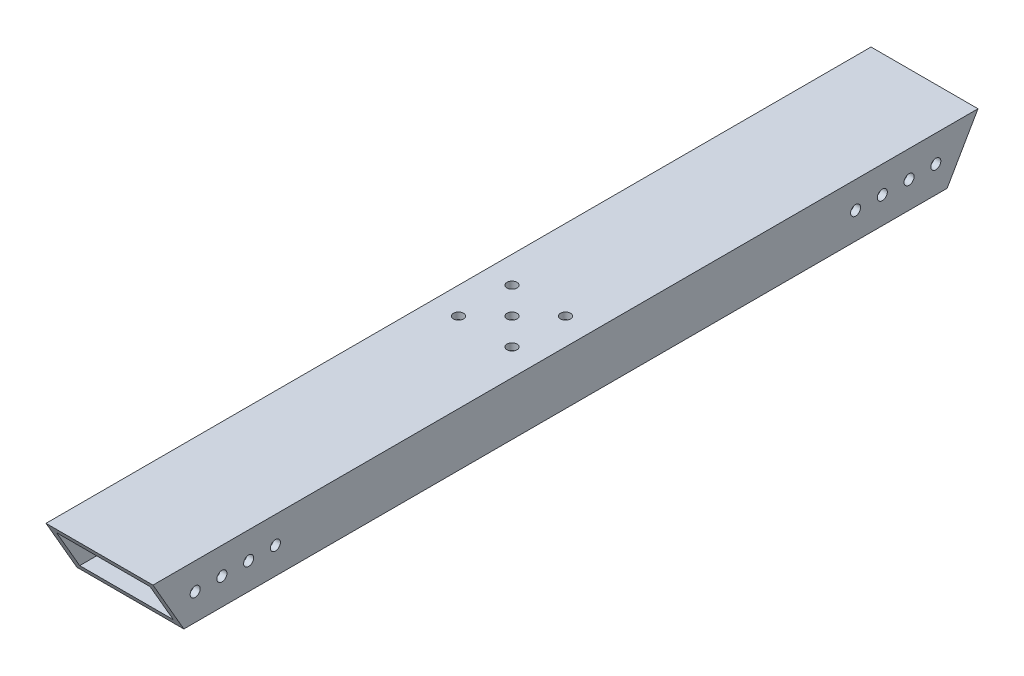
SolidWorks part; units mm, degrees
ref_plane "Front Plane" through (0, 0, 0) normal (0, 0, 1) x (1, 0, 0)
ref_plane "Top Plane" through (0, 0, 0) normal (0, 1, 0) x (1, 0, 0)
ref_plane "Right Plane" through (0, 0, 0) normal (1, 0, 0) x (0, 0, -1)
sketch "Sketch1" plane through (0, 0, 0) normal (0, 0, 1) x (1, 0, 0)
  line L0 (-22.225, 9.525) -> (22.225, 9.525)
  line L1 (-25.4, -12.7) -> (25.4, -12.7)
  line L2 (-25.4, -12.7) -> (-25.4, 12.7)
  line L3 (-25.4, 12.7) -> (25.4, 12.7)
  line L4 (25.4, -12.7) -> (25.4, 12.7)
  line L5 (-25.4, -12.7) -> (25.4, 12.7) construction
  line L6 (-25.4, 12.7) -> (25.4, -12.7) construction
  line L7 (22.225, -9.525) -> (22.225, 9.525)
  line L8 (-22.225, -9.525) -> (22.225, -9.525)
  line L9 (-22.225, -9.525) -> (-22.225, 9.525)
  point P0 (0, 0)
  dimension "D1" = 50.8
  dimension "D2" = 25.4
  dimension "D3" = 3.175
extrude "Boss-Extrude1" add sketch "Sketch1" along normal blind 391.7869
sketch "Sketch2" plane through (25.4, 0, 0) normal (1, 0, 0) x (0, 0, -1)
  line L0 (0, 12.7) -> (-14.6647, -12.7)
  line L1 (-391.7869, -12.7) -> (0, -12.7) construction
  line L2 (-14.6647, -12.7) -> (0, -12.7)
  line L3 (0, -12.7) -> (0, 12.7)
  line L4 (-195.8934, 12.7) -> (-195.8934, -12.7) construction
  line L5 (-391.7869, 12.7) -> (0, 12.7) construction
  line L6 (-391.7869, -12.7) -> (-391.7869, 12.7)
  line L7 (-377.1222, -12.7) -> (-391.7869, -12.7)
  line L8 (-391.7869, 12.7) -> (-377.1222, -12.7)
  dimension "D1" = 30
extrude "Cut-Extrude1" cut sketch "Sketch2" against normal blind 457.2
sketch "Sketch3" plane through (0, -12.7, 0) normal (0, -1, 0) x (-1, 0, 0)
  line L0 (25.4, -195.8934) -> (-25.4, -195.8934) construction
  line L1 (25.4, -377.1222) -> (25.4, -14.6647) construction
  line L2 (-25.4, -377.1222) -> (-25.4, -14.6647) construction
  line L3 (0, -377.1222) -> (0, -14.6647) construction
  line L4 (25.4, -377.1222) -> (-25.4, -377.1222) construction
  line L5 (25.4, -14.6647) -> (-25.4, -14.6647) construction
  circle A0 centre (0, -195.8934) radius 2.3812
  circle A1 centre (-12.7, -208.5934) radius 2.3812
  circle A2 centre (12.7, -208.5934) radius 2.3812
  circle A3 centre (-12.7, -183.1934) radius 2.3812
  circle A4 centre (12.7, -183.1934) radius 2.3812
  dimension "D1" = 4.7625
  dimension "D2" = 4.7625
  dimension "D3" = 12.7
  dimension "D4" = 12.7
extrude "Cut-Extrude2" cut sketch "Sketch3" against normal through all
sketch "Sketch4" plane through (-25.4, 0, 0) normal (-1, 0, 0) x (0, 0, 1)
  line L0 (195.8934, -12.7) -> (195.8934, 12.7) construction
  line L1 (377.1222, -12.7) -> (14.6647, -12.7) construction
  line L2 (391.7869, 12.7) -> (0, 12.7) construction
  circle A0 centre (195.8934, 0) radius 2.3813
  circle A1 centre (208.5934, 0) radius 2.3813
  circle A2 centre (183.1934, 0) radius 2.3813
  dimension "D1" = 4.7625
  dimension "D2" = 2
extrude "Cut-Extrude3" cut sketch "Sketch4" against normal blind 3.175
sketch "Sketch5" plane through (25.4, 0, 0) normal (1, 0, 0) x (0, 0, -1)
  line L0 (-195.8934, -12.7) -> (-195.8934, 12.7) construction
  line L1 (-377.1222, -12.7) -> (-14.6647, -12.7) construction
  line L2 (-391.7869, 12.7) -> (0, 12.7) construction
  line L3 (-397.1545, 0) -> (5.3677, 0) construction
  line L4 (-377.1222, -12.7) -> (-391.7869, 12.7) construction
  line L5 (-384.4545, 0) -> (-384.4545, 12.7) construction
  line L6 (-7.3323, 0) -> (-7.3323, 12.7) construction
  circle A0 centre (-371.7545, 0) radius 2.3813
  circle A1 centre (-359.0545, 0) radius 2.3813
  circle A2 centre (-346.3545, 0) radius 2.3813
  circle A3 centre (-333.6545, 0) radius 2.3813
  circle A4 centre (-58.1323, 0) radius 2.3813
  circle A5 centre (-45.4323, 0) radius 2.3813
  circle A6 centre (-32.7323, 0) radius 2.3813
  circle A7 centre (-20.0323, 0) radius 2.3813
  point P10 (-195.8934, 0)
  dimension "D2" = 4.7625
  dimension "D1" = 12.7
  dimension "D3" = 12.7
  dimension "D4" = 4
extrude "Cut-Extrude4" cut sketch "Sketch5" against normal through all
